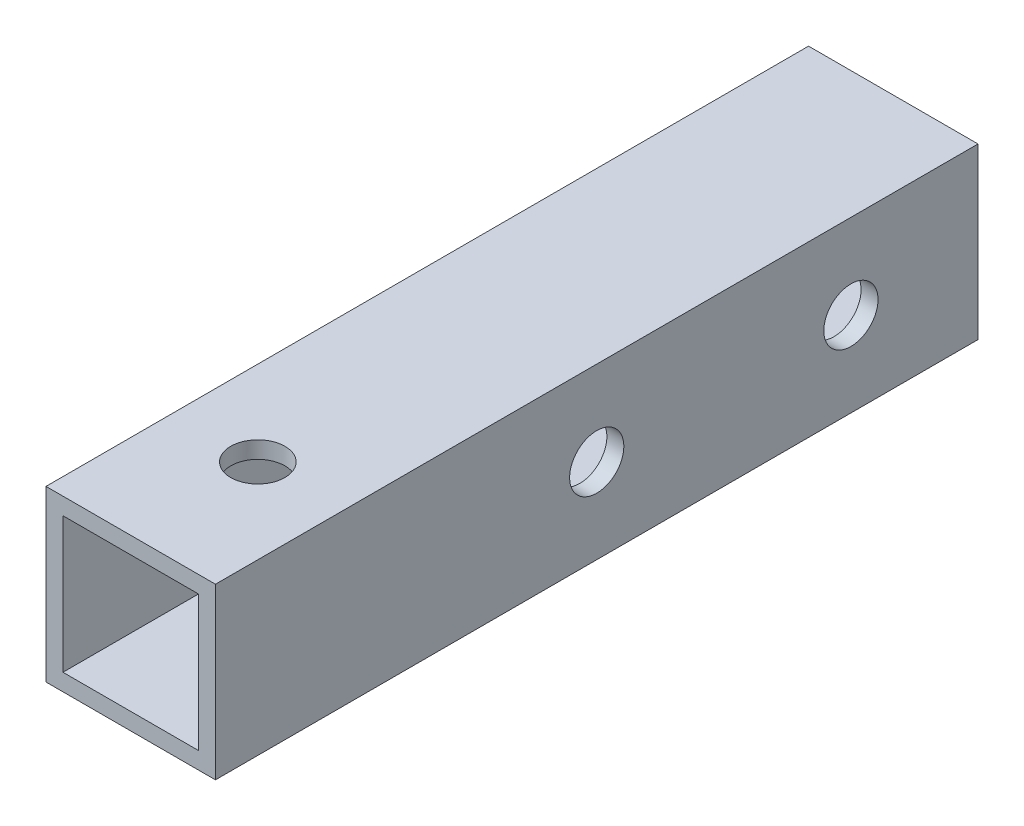
SolidWorks part; units mm, degrees
material "6063-T5"
ref_plane "正面" through (0, 0, 0) normal (0, 0, 1) x (1, 0, 0)
ref_plane "平面" through (0, 0, 0) normal (0, 1, 0) x (1, 0, 0)
ref_plane "右側面" through (0, 0, 0) normal (1, 0, 0) x (0, 0, -1)
sketch "ｽｹｯﾁ1" plane through (0, 0, 0) normal (0, 0, 1) x (1, 0, 0)
  line L1 (-5, -5) -> (5, -5)
  line L2 (-5, -5) -> (-5, 5)
  line L3 (-5, 5) -> (5, 5)
  line L4 (5, -5) -> (5, 5)
  line L5 (-5, -5) -> (5, 5) construction
  line L6 (-5, 5) -> (5, -5) construction
  point P0 (0, 0)
  dimension "D1" = 10
  dimension "D2" = 10
extrude "押し出し-薄板1" add sketch "ｽｹｯﾁ1" along normal blind 45 thin thin type one direction reverse wall 1
sketch "ｽｹｯﾁ2" plane through (0, 5, 0) normal (0, 1, 0) x (1, 0, 0)
  line L0 (0, 0) -> (0, -45) construction
  line L1 (5, -45) -> (-5, -45) construction
  line L2 (-5, -22.5) -> (5, -22.5) construction
  line L3 (-5, -45) -> (-5, 0) construction
  line L4 (5, -45) -> (5, 0) construction
  circle A0 centre (0, -37.5) radius 1.6
  circle A1 centre (0, -7.5) radius 1.6 construction
  dimension "D1" = 7.5
  dimension "D2" = 3.2
extrude "ｶｯﾄ - 押し出し1" cut sketch "ｽｹｯﾁ2" against normal through all
sketch "ｽｹｯﾁ3" plane through (5, 0, 0) normal (1, 0, 0) x (0, 0, -1)
  line L0 (-45, 0) -> (0, 0) construction
  line L1 (-45, -5) -> (-45, 5) construction
  line L2 (0, -5) -> (0, 5) construction
  line L3 (-22.5, 5) -> (-22.5, -5) construction
  line L4 (-45, 5) -> (0, 5) construction
  line L5 (-45, -5) -> (0, -5) construction
  circle A0 centre (-22.5, 0) radius 1.6
  circle A1 centre (-7.5, 0) radius 1.6
  dimension "D1" = 22.5
  dimension "D2" = 3.2
  dimension "D3" = 15
extrude "ｶｯﾄ - 押し出し2" cut sketch "ｽｹｯﾁ3" against normal through all
